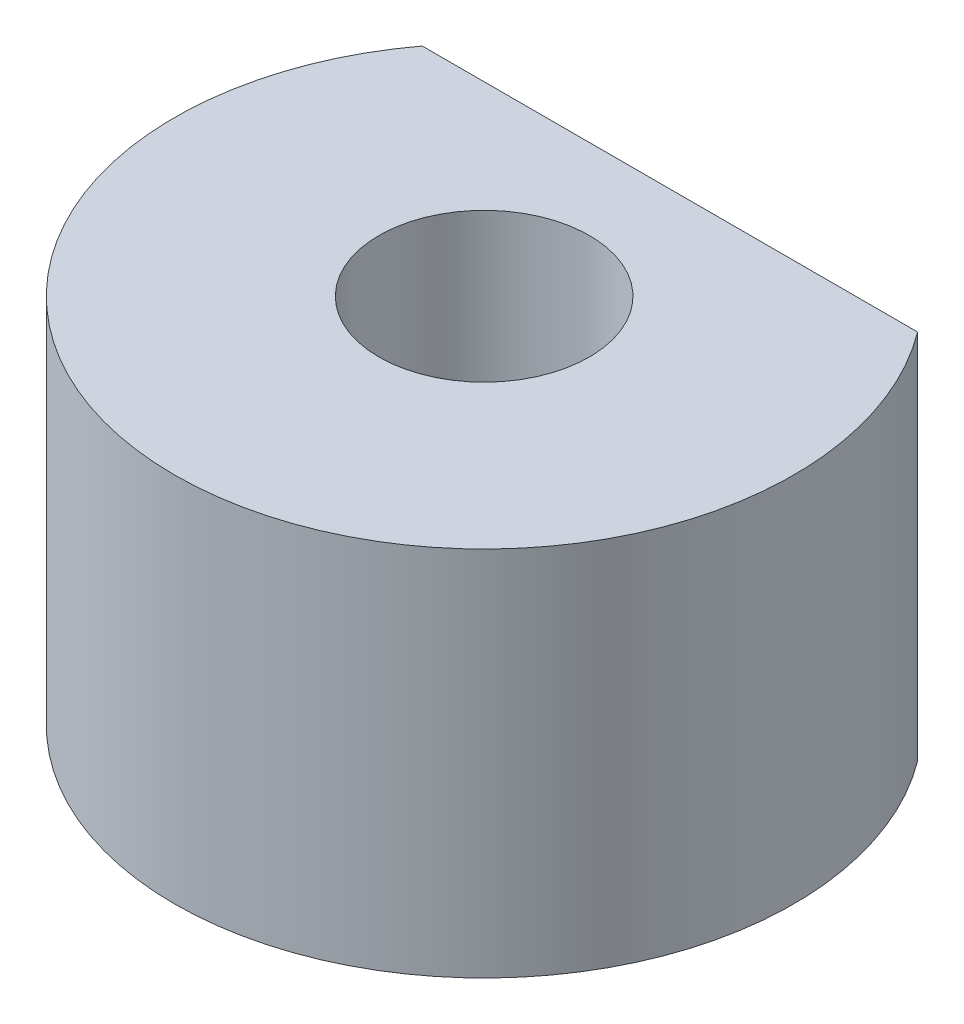
SolidWorks part; units mm, degrees
material "PETG"
ref_plane "Front Plane" through (0, 0, 0) normal (0, 0, 1) x (1, 0, 0)
ref_plane "Top Plane" through (0, 0, 0) normal (0, 1, 0) x (1, 0, 0)
ref_plane "Right Plane" through (0, 0, 0) normal (1, 0, 0) x (0, 0, -1)
sketch "Sketch1" plane through (0, 0, 0) normal (0, 1, 0) x (1, 0, 0)
  line L0 (-4, 3) -> (4, 3)
  circle A0 centre (0, 0) radius 1.7
  arc A1 (-4, 3) -> (4, 3) centre (0, 0) ccw
  dimension "D1" = 3.4
  dimension "D2" = 10
  dimension "D3" = 3
extrude "Boss-Extrude1" add sketch "Sketch1" along normal blind 6
